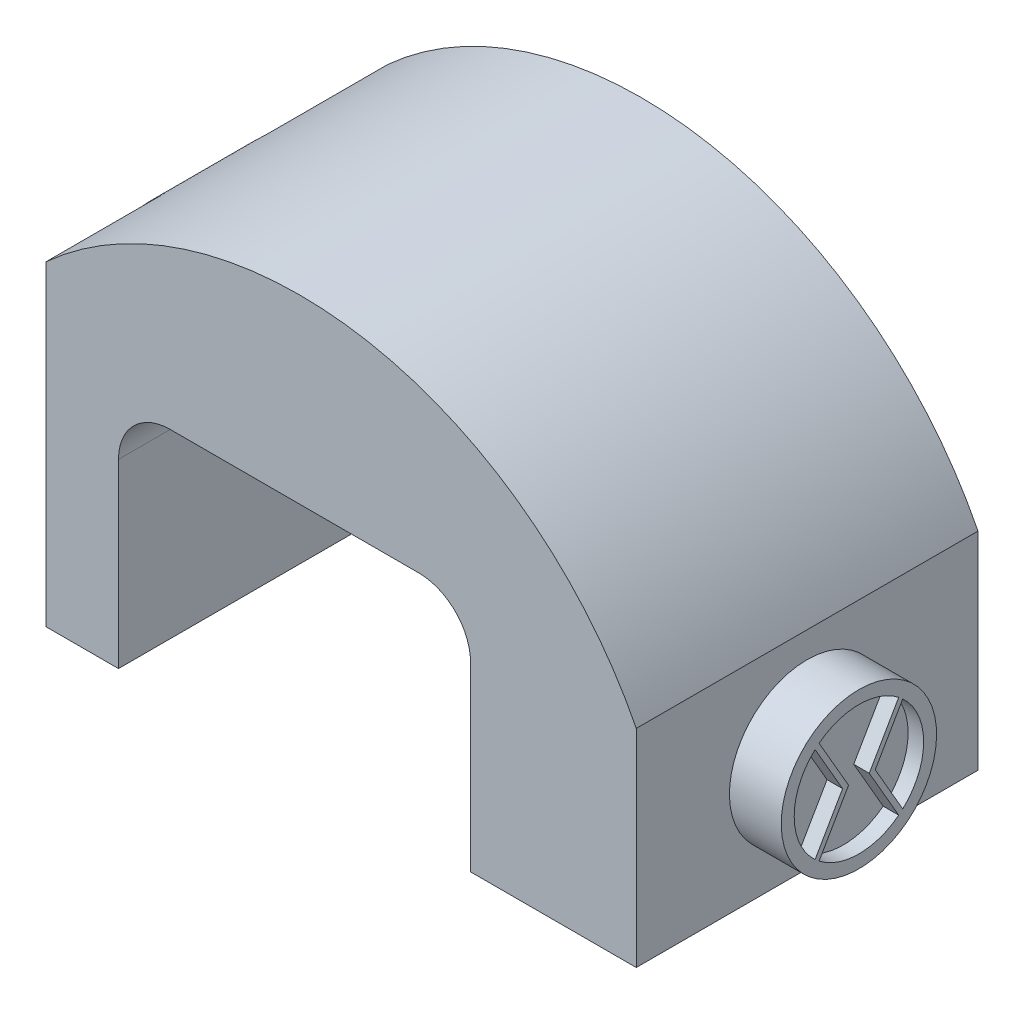
SolidWorks part; units mm, degrees
ref_plane "Front Plane" through (0, 0, 0) normal (0, 0, 1) x (1, 0, 0)
ref_plane "Top Plane" through (0, 0, 0) normal (0, 1, 0) x (1, 0, 0)
ref_plane "Right Plane" through (0, 0, 0) normal (1, 0, 0) x (0, 0, -1)
sketch "Sketch2" plane through (0, 0, 0) normal (0, 0, 1) x (1, 0, 0)
  line L1 (-65, 40) -> (65, 40)
  line L2 (-65, 40) -> (-65, -40)
  line L3 (-65, -40) -> (65, -40)
  line L4 (65, 40) -> (65, -40)
  line L5 (-65, 40) -> (65, -40) construction
  line L6 (-65, -40) -> (65, 40) construction
  arc A0 (-65, 0) -> (65, 0) centre (0, -32.8125) cw
  point P0 (0, 0)
  dimension "D1" = 130
  dimension "D2" = 80
extrude "Boss-Extrude1" add sketch "Sketch2" along normal blind 66 contours A0 L2 L3 L4
sketch "Sketch4" plane through (65, 0, 0) normal (1, 0, 0) x (0, 0, -1)
  line L0 (-66, 0) -> (0, 0) construction
  line L2 (0, 0) -> (0, -40) construction
  circle A0 centre (-33, -20) radius 15
  dimension "D1" = 30
  dimension "D2" = 20
  dimension "D3" = 33
extrude "Boss-Extrude2" add sketch "Sketch4" along normal blind 10
sketch "Sketch3" plane through (0, 0, 66) normal (0, 0, 1) x (1, 0, 0)
  line L0 (-65, -40) -> (65, -40) construction
  line L1 (-25, 5) -> (23, 5)
  line L2 (-35, -5) -> (-35, -40)
  line L3 (-35, -40) -> (33, -40)
  line L4 (33, -5) -> (33, -40)
  line L5 (-65, 0) -> (-65, -40) construction
  line L6 (65, 0) -> (65, -40) construction
  arc A1 (23, 5) -> (33, -5) centre (23, -5) cw
  arc A2 (-35, -5) -> (-25, 5) centre (-25, -5) cw
  point P12 (33, 5)
  dimension "D2" = 32
  dimension "D4" = 10
  dimension "D1" = 30
  dimension "D3" = 45
extrude "Cut-Extrude2" cut sketch "Sketch3" against normal through all
sketch "Sketch5" plane through (0, -40, 0) normal (0, -1, 0) x (1, 0, 0)
  line L9 (-65, 66) -> (-49, 66)
  line L10 (-65, 66) -> (-65, 43)
  line L11 (-65, 43) -> (-49, 43)
  line L12 (-49, 66) -> (-49, 43)
  line L13 (-65, 0) -> (-49, 0)
  line L14 (-65, 0) -> (-65, 23)
  line L15 (-65, 23) -> (-49, 23)
  line L16 (-49, 0) -> (-49, 23)
  dimension "D1" = 16
  dimension "D2" = 16
  dimension "D3" = 23
  dimension "D4" = 23
extrude "Cut-Extrude3" cut sketch "Sketch5" against normal through all
sketch "Sketch6" plane through (0, -40, 0) normal (0, -1, 0) x (1, 0, 0)
  line L0 (-65, 43) -> (-65, 23) construction
  line L1 (-53.5, 38) -> (-43.5, 38)
  line L2 (-53.5, 38) -> (-53.5, 28)
  line L3 (-53.5, 28) -> (-43.5, 28)
  line L4 (-43.5, 38) -> (-43.5, 28)
  line L5 (-65, 43) -> (-49, 43) construction
  dimension "D1" = 10
  dimension "D2" = 10
  dimension "D3" = 11.5
  dimension "D4" = 5
extrude "Boss-Extrude3" add sketch "Sketch6" along normal blind 5
sketch "Sketch7" plane through (0, -40, 0) normal (0, -1, 0) x (1, 0, 0)
  line L0 (65, 66) -> (65, 0) construction
  line L1 (35.5, 19.9) -> (47.5, 19.9)
  line L2 (35.5, 19.9) -> (35.5, 7.9)
  line L3 (35.5, 7.9) -> (47.5, 7.9)
  line L4 (47.5, 19.9) -> (47.5, 7.9)
  line L5 (33, 0) -> (65, 0) construction
  line L7 (47.5, 19.9) -> (47.5, 46.1) construction
  line L9 (47.5, 46.1) -> (35.5, 46.1)
  line L10 (47.5, 46.1) -> (47.5, 58.1)
  line L11 (47.5, 58.1) -> (35.5, 58.1)
  line L12 (35.5, 46.1) -> (35.5, 58.1)
  dimension "D1" = 17.5
  dimension "D2" = 7.9
  dimension "D3" = 12
  dimension "D4" = 26.2
  dimension "D5" = 12
extrude "Boss-Extrude4" add sketch "Sketch7" along normal blind 5
sketch "Sketch8" plane through (75, 0, 0) normal (1, 0, 0) x (0, 0, -1)
  line L0 (-33, -7.5) -> (-33, -32.5) construction
  line L1 (-33, -20) -> (-35, -20) construction
  line L2 (-35, -20) -> (-33, -20) construction
  line L3 (-33, -20) -> (-31, -20) construction
  line L4 (-35, -20) -> (-45.5, -20) construction
  line L5 (-45.5, -20) -> (-20.5, -20) construction
  line L6 (-33, -20) -> (-32.8575, -20.1004)
  line L7 (-35, -20) -> (-40.6897, -10.1451)
  line L8 (-40.6897, -10.1451) -> (-35, -20)
  line L9 (-35, -20) -> (-40.6897, -29.8549)
  line L10 (-36.1547, -20) -> (-41.5557, -29.3549)
  line L11 (-36.1547, -20) -> (-41.5557, -10.6451)
  line L12 (-33.8453, -20) -> (-39.8237, -30.3549)
  line L13 (-33.8453, -20) -> (-39.8237, -9.6451)
  line L14 (-31, -20) -> (-20.5, -20) construction
  line L15 (-32.1547, -20) -> (-26.1763, -9.6451)
  line L16 (-32.1547, -20) -> (-26.1763, -30.3549)
  line L17 (-29.8453, -20) -> (-24.4443, -10.6451)
  line L18 (-29.8453, -20) -> (-24.4443, -29.3549)
  line L19 (-31, -20) -> (-25.3103, -29.8549)
  line L20 (-25.3103, -10.1451) -> (-31, -20)
  line L21 (-31, -20) -> (-25.3103, -10.1451)
  circle A0 centre (-33, -20) radius 12.5
  dimension "D1" = 25
  dimension "D3" = 2
  dimension "D4" = 60
  dimension "D5" = 60
  dimension "D6" = 1
  dimension "D7" = 1
extrude "Cut-Extrude4" cut sketch "Sketch8" against normal blind 3
